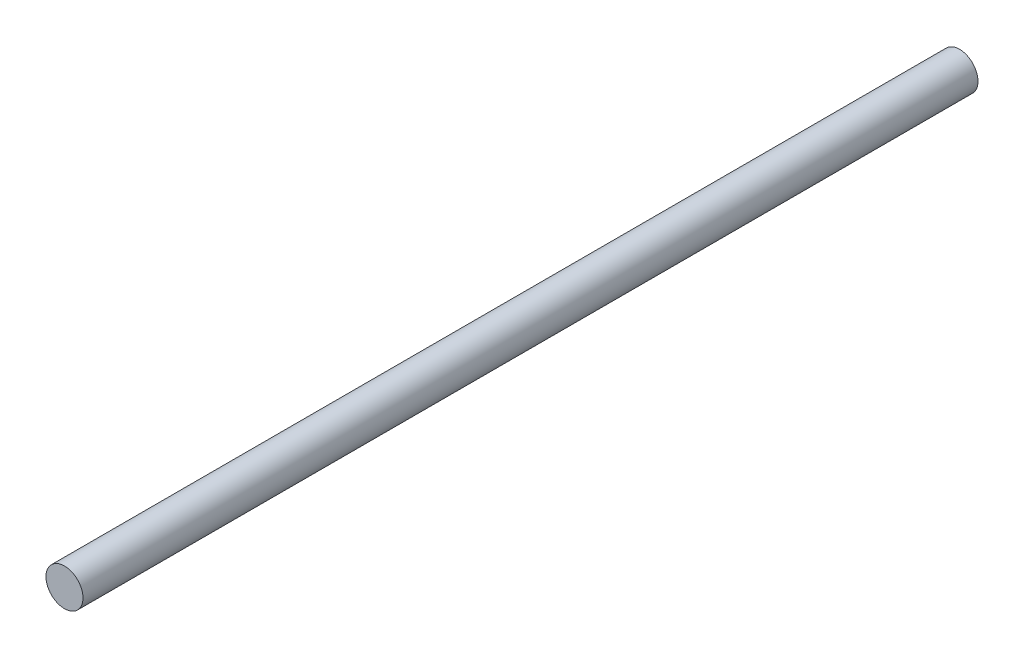
SolidWorks part; units mm, degrees
ref_plane "Front Plane" through (0, 0, 0) normal (0, 0, 1) x (1, 0, 0)
ref_plane "Top Plane" through (0, 0, 0) normal (0, 1, 0) x (1, 0, 0)
ref_plane "Right Plane" through (0, 0, 0) normal (1, 0, 0) x (0, 0, -1)
sketch "Sketch1" plane through (0, 0, 0) normal (0, 0, 1) x (1, 0, 0)
  circle A0 centre (0, 0) radius 6
  dimension "D1" = 12
extrude "Boss-Extrude1" add sketch "Sketch1" along normal blind 290
